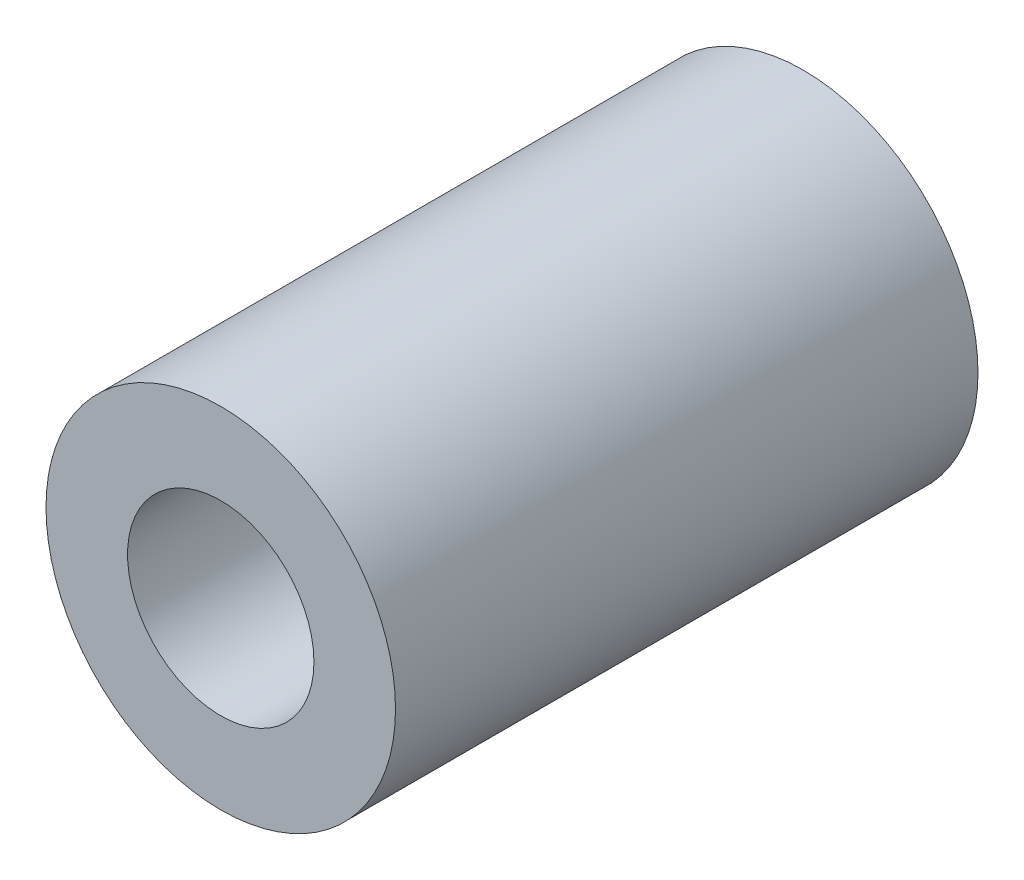
SolidWorks part; units mm, degrees
ref_plane "前视基准面" through (0, 0, 0) normal (0, 0, 1) x (1, 0, 0)
ref_plane "上视基准面" through (0, 0, 0) normal (0, 1, 0) x (1, 0, 0)
ref_plane "右视基准面" through (0, 0, 0) normal (1, 0, 0) x (0, 0, -1)
other "Configuration Table"
sketch "草图1" plane through (0, 0, 0) normal (0, 0, 1) x (1, 0, 0)
  circle A0 centre (0, 0) radius 3
  circle A1 centre (0, 0) radius 1.6
extrude "10mm铝柱" add sketch "草图1" along normal blind 10
